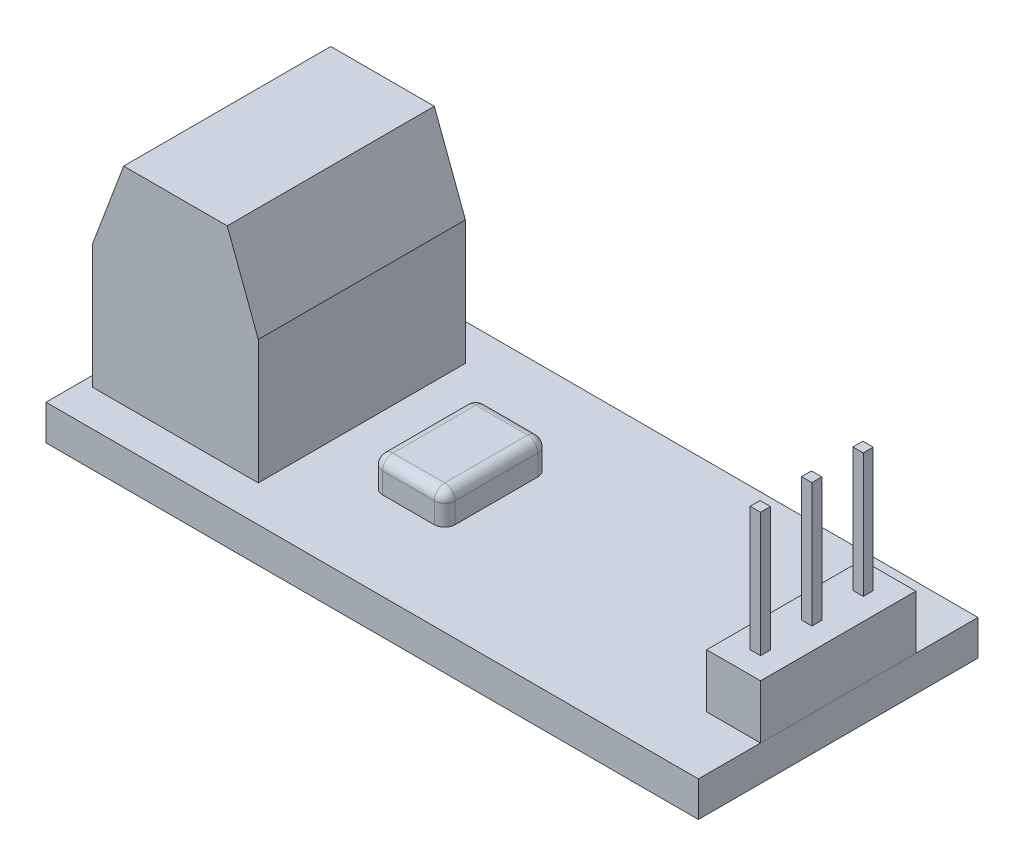
SolidWorks part; units mm, degrees
ref_plane "Alzado" through (0, 0, 0) normal (0, 0, 1) x (1, 0, 0)
ref_plane "Planta" through (0, 0, 0) normal (0, 1, 0) x (1, 0, 0)
ref_plane "Vista lateral" through (0, 0, 0) normal (1, 0, 0) x (0, 0, -1)
sketch "Croquis1" plane through (0, 0, 0) normal (0, 1, 0) x (1, 0, 0)
  line L1 (-15.75, 6.75) -> (15.75, 6.75)
  line L2 (-15.75, 6.75) -> (-15.75, -6.75)
  line L3 (-15.75, -6.75) -> (15.75, -6.75)
  line L4 (15.75, 6.75) -> (15.75, -6.75)
  line L5 (-15.75, 6.75) -> (15.75, -6.75) construction
  line L6 (-15.75, -6.75) -> (15.75, 6.75) construction
  point P0 (0, 0)
  dimension "D1" = 31.5
  dimension "D2" = 13.5
extrude "Saliente-Extruir1" add sketch "Croquis1" along normal blind 1.7
sketch "Croquis2" plane through (0, 1.7, 0) normal (0, 1, 0) x (1, 0, 0)
  line L0 (15.75, -6.75) -> (15.75, 6.75) construction
  line L1 (13.15, 3.75) -> (15.75, 3.75)
  line L2 (13.15, 3.75) -> (13.15, -3.75)
  line L3 (13.15, -3.75) -> (15.75, -3.75)
  line L4 (15.75, 3.75) -> (15.75, -3.75)
  point P6 (13.15, 0)
  dimension "D1" = 2.6
  dimension "D2" = 7.5
extrude "Saliente-Extruir2" add sketch "Croquis2" along normal blind 2.6 separate body
sketch "Croquis3" plane through (0, 4.3, 0) normal (0, 1, 0) x (1, 0, 0)
  line L0 (13.15, 1.25) -> (15.75, 1.25) construction
  line L1 (13.15, 3.75) -> (13.15, -3.75) construction
  line L2 (15.75, -3.75) -> (15.75, 3.75) construction
  line L3 (15.75, 3.75) -> (13.15, 3.75) construction
  line L4 (13.15, -1.25) -> (15.75, -1.25) construction
  line L5 (13.15, -3.75) -> (15.75, -3.75) construction
  line L6 (13.15, 3.75) -> (15.75, 1.25) construction
  line L7 (13.15, 1.25) -> (15.75, 3.75) construction
  line L8 (14.2, 0.2596) -> (14.2, -0.2212)
  line L9 (14.2, 2.7404) -> (14.7, 2.7404)
  line L10 (14.2, 2.7404) -> (14.2, 2.2596)
  line L11 (14.2, 2.2596) -> (14.7, 2.2596)
  line L12 (14.7, 2.7404) -> (14.7, 2.2596)
  line L13 (14.2, 2.7404) -> (14.7, 2.2596) construction
  line L14 (14.2, 2.2596) -> (14.7, 2.7404) construction
  line L15 (14.2, 0.2596) -> (14.7, 0.2596)
  line L16 (14.7, 0.2596) -> (14.7, -0.2212)
  line L17 (14.2, -0.2212) -> (14.7, -0.2212)
  line L18 (14.2, -2.2212) -> (14.2, -2.7019)
  line L19 (14.2, -2.2212) -> (14.7, -2.2212)
  line L20 (14.7, -2.2212) -> (14.7, -2.7019)
  line L21 (14.2, -2.7019) -> (14.7, -2.7019)
  point P13 (14.45, 2.5)
  dimension "D1" = 2.5
  dimension "D2" = 2.5
  dimension "D3" = 0.5
  dimension "D5" = 2
  dimension "D4" = 3
extrude "Saliente-Extruir3" add sketch "Croquis3" along normal blind 6 separate body
sketch "Croquis4" plane through (0, 1.7, 0) normal (0, 1, 0) x (1, 0, 0)
  line L0 (-15.75, 6.75) -> (-15.75, -6.75) construction
  line L1 (-15.25, 5) -> (-7.25, 5)
  line L2 (-15.25, 5) -> (-15.25, -5)
  line L3 (-15.25, -5) -> (-7.25, -5)
  line L4 (-7.25, 5) -> (-7.25, -5)
  point P4 (-7.25, 0)
  dimension "D1" = 0.5
  dimension "D2" = 8
  dimension "D3" = 10
extrude "Saliente-Extruir4" add sketch "Croquis4" along normal blind 10 separate body
sketch "Croquis5" plane through (0, 0, 5) normal (0, 0, 1) x (1, 0, 0)
  line L0 (-11.25, 1.7) -> (-11.25, 11.7) construction
  line L1 (-15.25, 1.7) -> (-7.25, 1.7) construction
  line L2 (-15.25, 11.7) -> (-7.25, 11.7) construction
  line L3 (-8.75, 11.7) -> (-7.25, 7.7)
  line L4 (-7.25, 11.7) -> (-7.25, 1.7) construction
  line L5 (-7.25, 7.7) -> (-7.25, 11.7)
  line L6 (-7.25, 11.7) -> (-8.75, 11.7)
  line L7 (-15.25, 7.7) -> (-15.25, 11.7)
  line L8 (-13.75, 11.7) -> (-15.25, 7.7)
  line L9 (-15.25, 11.7) -> (-13.75, 11.7)
  dimension "D1" = 1.5
  dimension "D2" = 4
extrude "Cortar-Extruir1" cut sketch "Croquis5" against normal through all
sketch "Croquis6" plane through (0, 1.7, 0) normal (0, 1, 0) x (1, 0, 0)
  line L0 (-7.25, 5) -> (-7.25, -5) construction
  line L1 (-4.25, 2.5) -> (-0.75, 2.5)
  line L2 (-4.25, 2.5) -> (-4.25, -2.5)
  line L3 (-4.25, -2.5) -> (-0.75, -2.5)
  line L4 (-0.75, 2.5) -> (-0.75, -2.5)
  point P4 (-0.75, 0)
  dimension "D1" = 3.5
  dimension "D2" = 5
  dimension "D3" = 3
extrude "Saliente-Extruir5" add sketch "Croquis6" along normal blind 1.5 separate body
fillet "Redondeo1" radius 0.5 8 edges at (-4.25, 2.45, -2.5) (-0.75, 2.45, -2.5) (-4.25, 2.45, 2.5) (-0.75, 2.45, 2.5) (-2.5, 3.2, -2.5) (-4.25, 3.2, 0) (-2.5, 3.2, 2.5) (-0.75, 3.2, 0)
